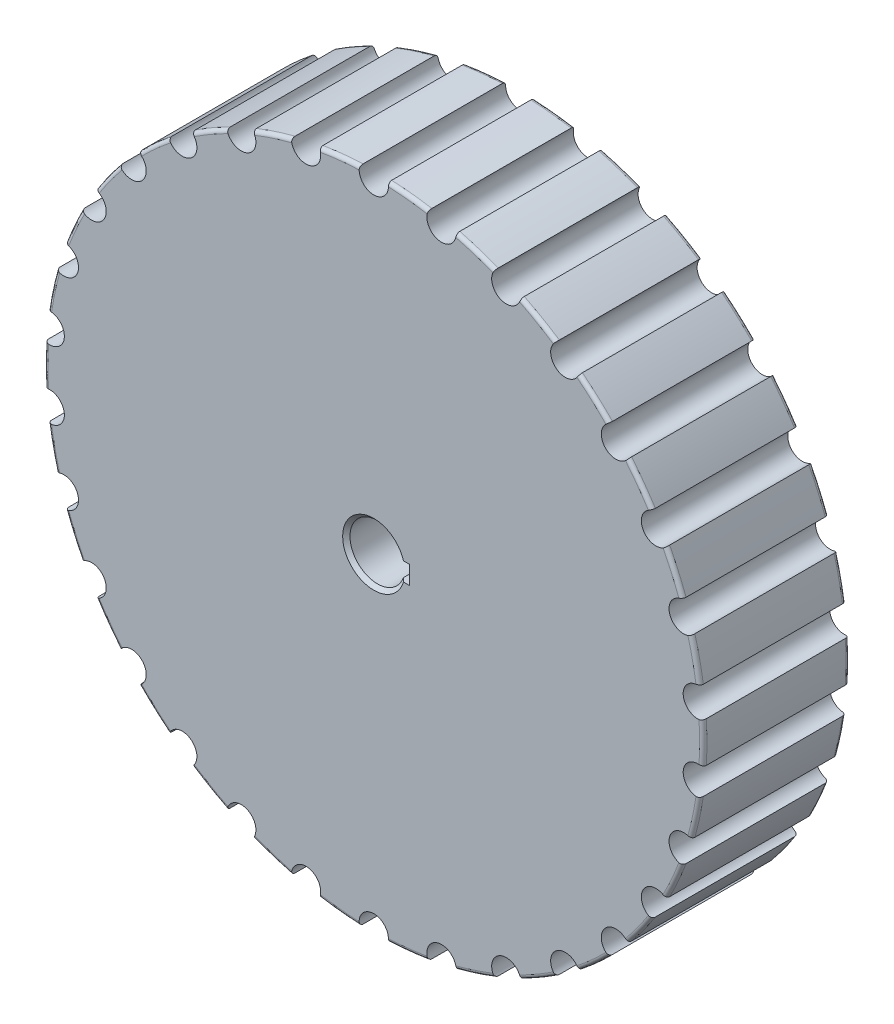
SolidWorks part; units mm, degrees
ref_plane "前视基准面" through (0, 0, 0) normal (0, 0, 1) x (1, 0, 0)
ref_plane "上视基准面" through (0, 0, 0) normal (0, 1, 0) x (1, 0, 0)
ref_plane "右视基准面" through (0, 0, 0) normal (1, 0, 0) x (0, 0, -1)
other "Configuration Table"
sketch "草图1" plane through (0, 0, 0) normal (0, 1, 0) x (1, 0, 0)
  line L0 (90, 20) -> (0, 20)
  line L1 (0, 20) -> (0, -20)
  line L2 (0, -20) -> (90, -20)
  line L3 (90, -20) -> (90, 20)
  line L4 (0, 20) -> (0, -20) construction
revolve "旋转1" add sketch "草图1" angle 360 about L4
hole_wizard "孔1" positions "草图3" profile "草图2" legacy
sketch "草图3" plane through (0, 0, -20) normal (0, 0, -1) x (-1, 0, 0)
  point P0 (0, 0)
sketch "草图2" plane through (0, 0, -20) normal (1, 0, 0) x (0, 1, 0)
  line L0 (0, 0) -> (0, 16)
  line L1 (0, 16) -> (75, 16)
  line L2 (75, 16) -> (75, 0)
  line L3 (75, 0) -> (0, 0)
  line L4 (0, 110) -> (0, -10) construction
  dimension "直径" = 150
  dimension "深度" = 16
sketch "草图4" plane through (0, 0, -4) normal (0, 0, -1) x (-1, 0, 0)
  circle A0 centre (0, 0) radius 30
extrude "凸台-拉伸1" add sketch "草图4" along normal blind 16
sketch "草图5" plane through (0, 0, 20) normal (0, 0, 1) x (1, 0, 0)
  line L0 (9.8, -2.5) -> (9.8, 2.5)
  line L1 (9.8, 2.5) -> (7.0711, 2.5)
  line L2 (7.0711, -2.5) -> (9.8, -2.5)
  arc A0 (7.0711, 2.5) -> (7.0711, -2.5) centre (0, 0) cw
extrude "切除-拉伸1" cut sketch "草图5" against normal blind 28
ref_plane "基准面1" through (0, 0, 0) normal (0, -1, 0) x (1, 0, 0)
sketch "草图6" plane through (0, 0, 0) normal (0, -1, 0) x (1, 0, 0)
  line L0 (7.5, 20) -> (0, 20)
  line L1 (0, 20) -> (0, -20)
  line L2 (0, -20) -> (25.5, -20)
  line L3 (25.5, -20) -> (25.5, -8)
  line L4 (25.5, -8) -> (7.5, -8)
  line L5 (7.5, -8) -> (7.5, 20)
  line L6 (0, 20) -> (0, -20) construction
revolve "切除-旋转1" cut sketch "草图6" angle 360 about L6
hole_wizard "Ø8.0 (8) 直径孔1" positions "草图8" profile "草图7" hole size "Ø8.0" standard "ANSI Metric"
sketch "草图8" plane through (0, 0, -20) normal (0, 0, -1) x (-1, 0, 0)
  point P0 (-36.1996, -81.3055)
  point P1 (-52.3129, -72.0025)
  point P2 (-66.1399, -59.5526)
  point P3 (-77.0763, -44.5)
  point P4 (-84.644, -27.5025)
  point P5 (-84.644, 27.5025)
  point P6 (-18.5041, 87.0551)
  point P7 (0, 89)
  point P8 (18.5041, 87.0551)
  point P9 (36.1996, 81.3055)
  point P10 (52.3129, 72.0025)
  point P11 (66.1399, 59.5526)
  point P12 (77.0763, 44.5)
  point P13 (84.644, 27.5025)
  point P14 (88.5124, 9.303)
  point P15 (88.5124, -9.303)
  point P16 (84.644, -27.5025)
  point P17 (77.0763, -44.5)
  point P18 (66.1399, -59.5526)
  point P19 (52.3129, -72.0025)
  point P20 (36.1996, -81.3055)
  point P21 (18.5041, -87.0551)
  point P22 (0, -89)
  point P23 (-18.5041, -87.0551)
sketch "草图7" plane through (36.1996, -81.3055, -20) normal (1, 0, 0) x (0, 1, 0)
  line L0 (0, 0) -> (0, 40)
  line L1 (0, 40) -> (4, 40)
  line L2 (4, 40) -> (4, 0)
  line L5 (4, 0) -> (0, 0)
  line L11 (0, -6.35) -> (0, 107.95) construction
  dimension "通孔孔直径" = 8
  dimension "通孔孔深度" = 40
hole_wizard "Ø8.0 (8) 直径孔2" positions "草图10" profile "草图9" hole size "Ø8.0" standard "ANSI Metric"
sketch "草图10" plane through (0, 0, 20) normal (0, 0, 1) x (1, 0, 0)
  point P0 (36.1996, 81.3055)
  point P1 (88.5124, -9.303)
  point P2 (88.5124, 9.303)
  point P3 (77.0763, 44.5)
  point P4 (66.1399, 59.5526)
  point P5 (52.3129, 72.0025)
sketch "草图9" plane through (36.1996, 81.3055, 20) normal (1, 0, 0) x (0, -1, 0)
  line L0 (0, 0) -> (0, 40)
  line L1 (0, 40) -> (4, 40)
  line L2 (4, 40) -> (4, 0)
  line L5 (4, 0) -> (0, 0)
  line L11 (0, -6.35) -> (0, 107.95) construction
  dimension "通孔孔直径" = 8
  dimension "通孔孔深度" = 40
hole_wizard "Ø3.3 (3.3) 直径孔1" positions "草图12" profile "草图11" hole size "Ø3.3" standard "ANSI Metric"
sketch "草图12" plane through (0, 0, -8) normal (0, 0, -1) x (-1, 0, 0)
  point P0 (20, 0)
  point P1 (0, 20)
  point P2 (-20, 0)
  point P3 (0, -20)
sketch "草图11" plane through (-20, 0, -8) normal (1, 0, 0) x (0, 1, 0)
  line L0 (0, 0) -> (0, 4)
  line L1 (0, 4) -> (1.65, 4)
  line L2 (1.65, 4) -> (1.65, 0)
  line L5 (1.65, 0) -> (0, 0)
  line L10 (0, 4) -> (-1.65, 4) construction
  line L11 (0, -6.35) -> (0, 107.95) construction
  dimension "孔直径" = 3.3
  dimension "孔深度" = 4
  dimension "导头角度" = 180
chamfer "倒角1" distance 1 angle 45 2 edges at (-7.5, 0, -8) (-7.5, 0, 20)
fillet "圆角1" radius 1 60 edges at (-9.4076, 89.507, 20) (27.8115, -85.5951, 20) (-88.0333, -18.7121, 20) (9.4076, 89.507, -20) (72.8115, 52.9007, 20) (-9.4076, 89.507, -20) (-72.8115, 52.9007, 20) (-27.8115, 85.5951, -20) (-45, -77.9423, 20) (-45, 77.9423, -20) (82.2191, -36.6063, 20) (-60.2218, 66.883, -20) (90, 0, 20) (-72.8115, 52.9007, -20) (-45, 77.9423, 20) (-82.2191, 36.6063, -20) (-88.0333, 18.7121, 20) (-88.0333, 18.7121, -20) (-72.8115, -52.9007, 20) (-90, 0, -20) (-9.4076, -89.507, 20) (-88.0333, -18.7121, -20) (60.2218, -66.883, 20) (-82.2191, -36.6063, -20) (88.0333, 18.7121, 20) (-72.8115, -52.9007, -20) (45, 77.9423, 20) (-60.2218, -66.883, -20) (9.4076, 89.507, 20) (-45, -77.9423, -20) (-27.8115, 85.5951, 20) (-27.8115, -85.5951, -20) (-60.2218, 66.883, 20) (-9.4076, -89.507, -20) (-82.2191, 36.6063, 20) (9.4076, -89.507, -20) (-90, 0, 20) (27.8115, -85.5951, -20) (-82.2191, -36.6063, 20) (45, -77.9423, -20) (-60.2218, -66.883, 20) (60.2218, -66.883, -20) (-27.8115, -85.5951, 20) (72.8115, -52.9007, -20) (9.4076, -89.507, 20) (82.2191, -36.6063, -20) (45, -77.9423, 20) (88.0333, -18.7121, -20) (72.8115, -52.9007, 20) (88.0333, 18.7121, -20) (88.0333, -18.7121, 20) (82.2191, 36.6063, -20) (82.2191, 36.6063, 20) (72.8115, 52.9007, -20) (60.2218, 66.883, 20) (27.8115, 85.5951, -20) (90, 0, -20) (60.2218, 66.883, -20) (27.8115, 85.5951, 20) (45, 77.9423, -20)
